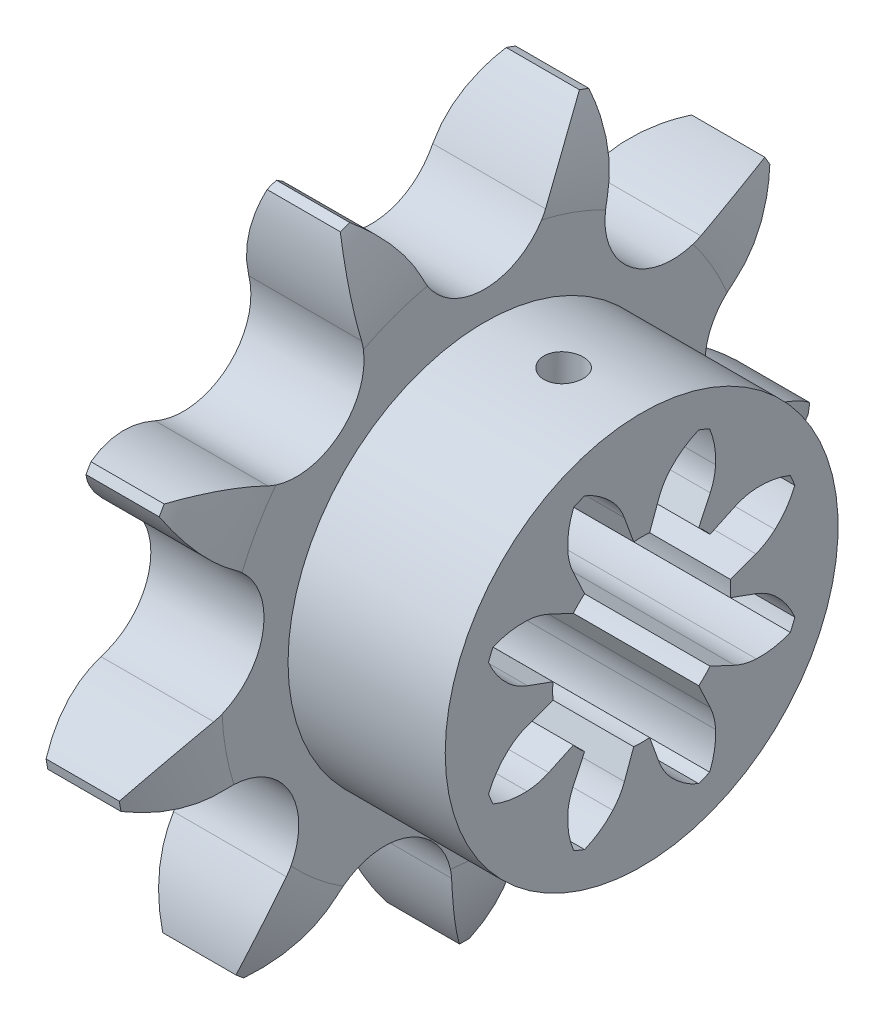
SolidWorks part; units mm, degrees
material "Barra Redonda SAE 1020 - 2\""
ref_plane "Plano frontal" through (0, 0, 0) normal (0, 0, 1) x (1, 0, 0)
ref_plane "Plano superior" through (0, 0, 0) normal (0, 1, 0) x (1, 0, 0)
ref_plane "Plano direito" through (0, 0, 0) normal (1, 0, 0) x (0, 0, -1)
sketch "Esboço1" plane through (0, 0, 0) normal (0, 0, 1) x (1, 0, 0)
  line L0 (-35, 0) -> (0, 0) construction
  line L1 (0, 0) -> (0, 16.7129)
  line L2 (0, 0) -> (17.2, 0)
  line L3 (7.2, 12.5) -> (7.2, 16.7129)
  line L4 (5.93, 22.2487) -> (1.27, 22.2487)
  line L5 (17.2, 0) -> (35, 0) construction
  line L8 (7.2, 12.5) -> (17.2, 12.5)
  line L9 (17.2, 0) -> (17.2, 12.5)
  arc A0 (0, 16.7129) -> (1.27, 22.2487) centre (12.7, 16.7129) cw
  arc A1 (7.2, 16.7129) -> (5.93, 22.2487) centre (-5.5, 16.7129) ccw
  dimension "D4" = 12.7
  dimension "D1" = 1.27
  dimension "D2" = 1.27
  dimension "D3" = 7.2
  dimension "D5" = 44.4973
  dimension "D6" = 10
  dimension "D7" = 25
revolve "Revolução1" add sketch "Esboço1" angle 360 about L0
sketch "Esboço2" plane through (7.2, 0, 0) normal (1, 0, 0) x (0, 0, -1)
  line L0 (0, 18.6087) -> (3.8949, 16.7925) construction
  line L1 (0, 0) -> (0, 63.7114) construction
  line L2 (0, 18.6087) -> (-10, 18.6087) construction
  line L3 (0, 18.6087) -> (-3.8949, 16.7925) construction
  arc A0 (3.8949, 16.7925) -> (7.8075, 21.3669) centre (14.0756, 12.0451) cw
  arc A1 (3.8949, 16.7925) -> (-3.8949, 16.7925) centre (0, 18.6087) cw
  arc A2 (-3.8949, 16.7925) -> (-7.8075, 21.3669) centre (-14.0756, 12.0451) ccw
  arc A3 (7.8075, 21.3669) -> (-7.8075, 21.3669) centre (0, 0) ccw
  dimension "D2" = 4.2976
  dimension "D4" = 11.2332
  dimension "D5" = 22.7487
  dimension "D1" = 18.6087
  dimension "D3" = 130
extrude "Corte-extrusão1" cut sketch "Esboço2" against normal through all
pattern_circular "PadrãoCircular1" count 9 over 360 about axis through (0, 0, 0) along (1, 0, 0) of "Corte-extrusão1"
sketch "Esboço3" plane through (7.2, 0, 0) normal (1, 0, 0) x (0, 0, -1)
  line L0 (0, 0) -> (0, 12.1456) construction
  line L1 (-0.5068, 5.6423) -> (0, 4.25) construction
  line L2 (-0.5068, 5.6423) -> (-1.0979, 7.2665)
  line L3 (0.5068, 5.6423) -> (1.0979, 7.2665)
  line L4 (3.6314, 4.348) -> (4.3619, 5.9145)
  line L5 (4.348, 3.6314) -> (5.9145, 4.3619)
  line L6 (5.6423, 0.5068) -> (7.2665, 1.0979)
  line L7 (5.6423, -0.5068) -> (7.2665, -1.0979)
  line L8 (4.348, -3.6314) -> (5.9145, -4.3619)
  line L9 (3.6314, -4.348) -> (4.3619, -5.9145)
  line L10 (0.5068, -5.6423) -> (1.0979, -7.2665)
  line L11 (-0.5068, -5.6423) -> (-1.0979, -7.2665)
  line L12 (-3.6314, -4.348) -> (-4.3619, -5.9145)
  line L13 (-4.348, -3.6314) -> (-5.9145, -4.3619)
  line L14 (-5.6423, -0.5068) -> (-7.2665, -1.0979)
  line L15 (-5.6423, 0.5068) -> (-7.2665, 1.0979)
  line L16 (-4.348, 3.6314) -> (-5.9145, 4.3619)
  line L17 (-3.6314, 4.348) -> (-4.3619, 5.9145)
  arc A0 (-9.4582, 4.3245) -> (-9.7459, 3.6301) centre (0, 0) ccw construction
  circle A1 centre (0, 0) radius 7.54 construction
  circle A2 centre (0, 0) radius 5.665 construction
  circle A3 centre (0, 0) radius 4.25 construction
  arc A4 (-3.6301, 9.7459) -> (-1.833, 8.4832) centre (-5.5475, 5.1065) cw
  arc A5 (1.833, 8.4832) -> (1.0979, 7.2665) centre (4.556, 6.0079) ccw
  arc A6 (-1.833, 8.4832) -> (-1.0979, 7.2665) centre (-4.556, 6.0079) cw
  arc A7 (3.6301, 9.7459) -> (1.833, 8.4832) centre (5.5475, 5.1065) ccw
  arc A8 (-0.5068, 5.6423) -> (0.5068, 5.6423) centre (0, 0) cw
  arc A9 (4.3245, 9.4582) -> (3.6301, 9.7459) centre (0, 0) ccw construction
  arc A10 (9.7459, 3.6301) -> (9.4582, 4.3245) centre (0, 0) ccw
  arc A11 (4.3245, 9.4582) -> (4.7025, 7.2947) centre (-0.3118, 7.5335) cw
  arc A12 (9.4582, 4.3245) -> (7.2947, 4.7025) centre (7.5335, -0.3118) ccw
  arc A13 (7.2947, 4.7025) -> (5.9145, 4.3619) centre (7.4698, 1.0266) ccw
  arc A14 (4.7025, 7.2947) -> (4.3619, 5.9145) centre (1.0266, 7.4698) cw
  arc A15 (3.6314, 4.348) -> (4.348, 3.6314) centre (0, 0) cw
  arc A16 (9.4582, -4.3245) -> (9.7459, -3.6301) centre (0, 0) ccw
  arc A17 (9.7459, 3.6301) -> (8.4832, 1.833) centre (5.1065, 5.5475) cw
  arc A18 (9.7459, -3.6301) -> (8.4832, -1.833) centre (5.1065, -5.5475) ccw
  arc A19 (8.4832, -1.833) -> (7.2665, -1.0979) centre (6.0079, -4.556) ccw
  arc A20 (8.4832, 1.833) -> (7.2665, 1.0979) centre (6.0079, 4.556) cw
  arc A21 (5.6423, 0.5068) -> (5.6423, -0.5068) centre (0, 0) cw
  arc A22 (3.6301, -9.7459) -> (4.3245, -9.4582) centre (0, 0) ccw
  arc A23 (9.4582, -4.3245) -> (7.2947, -4.7025) centre (7.5335, 0.3118) cw
  arc A24 (4.3245, -9.4582) -> (4.7025, -7.2947) centre (-0.3118, -7.5335) ccw
  arc A25 (4.7025, -7.2947) -> (4.3619, -5.9145) centre (1.0266, -7.4698) ccw
  arc A26 (7.2947, -4.7025) -> (5.9145, -4.3619) centre (7.4698, -1.0266) cw
  arc A27 (4.348, -3.6314) -> (3.6314, -4.348) centre (0, 0) cw
  arc A28 (-4.3245, -9.4582) -> (-3.6301, -9.7459) centre (0, 0) ccw
  arc A29 (3.6301, -9.7459) -> (1.833, -8.4832) centre (5.5475, -5.1065) cw
  arc A30 (-3.6301, -9.7459) -> (-1.833, -8.4832) centre (-5.5475, -5.1065) ccw
  arc A31 (-1.833, -8.4832) -> (-1.0979, -7.2665) centre (-4.556, -6.0079) ccw
  arc A32 (1.833, -8.4832) -> (1.0979, -7.2665) centre (4.556, -6.0079) cw
  arc A33 (0.5068, -5.6423) -> (-0.5068, -5.6423) centre (0, 0) cw
  arc A34 (-9.7459, -3.6301) -> (-9.4582, -4.3245) centre (0, 0) ccw
  arc A35 (-4.3245, -9.4582) -> (-4.7025, -7.2947) centre (0.3118, -7.5335) cw
  arc A36 (-9.4582, -4.3245) -> (-7.2947, -4.7025) centre (-7.5335, 0.3118) ccw
  arc A37 (-7.2947, -4.7025) -> (-5.9145, -4.3619) centre (-7.4698, -1.0266) ccw
  arc A38 (-4.7025, -7.2947) -> (-4.3619, -5.9145) centre (-1.0266, -7.4698) cw
  arc A39 (-3.6314, -4.348) -> (-4.348, -3.6314) centre (0, 0) cw
  arc A41 (-9.7459, -3.6301) -> (-8.4832, -1.833) centre (-5.1065, -5.5475) cw
  arc A42 (-9.7459, 3.6301) -> (-8.4832, 1.833) centre (-5.1065, 5.5475) ccw
  arc A43 (-8.4832, 1.833) -> (-7.2665, 1.0979) centre (-6.0079, 4.556) ccw
  arc A44 (-8.4832, -1.833) -> (-7.2665, -1.0979) centre (-6.0079, -4.556) cw
  arc A45 (-5.6423, -0.5068) -> (-5.6423, 0.5068) centre (0, 0) cw
  arc A46 (-3.6301, 9.7459) -> (-4.3245, 9.4582) centre (0, 0) ccw construction
  arc A47 (-9.4582, 4.3245) -> (-7.2947, 4.7025) centre (-7.5335, -0.3118) cw
  arc A48 (-4.3245, 9.4582) -> (-4.7025, 7.2947) centre (0.3118, 7.5335) ccw
  arc A49 (-4.7025, 7.2947) -> (-4.3619, 5.9145) centre (-1.0266, 7.4698) ccw
  arc A50 (-7.2947, 4.7025) -> (-5.9145, 4.3619) centre (-7.4698, 1.0266) cw
  arc A51 (-4.348, 3.6314) -> (-3.6314, 4.348) centre (0, 0) cw
  arc A52 (-9.4582, 4.3245) -> (-9.7459, 3.6301) centre (0, 0) ccw
  arc A54 (-3.6301, 9.7459) -> (-4.3245, 9.4582) centre (0, 0) ccw
  arc A55 (4.3245, 9.4582) -> (3.6301, 9.7459) centre (0, 0) ccw
  arc A56 (9.7459, 3.6301) -> (9.4582, 4.3245) centre (0, 0) ccw construction
  arc A57 (9.4582, -4.3245) -> (9.7459, -3.6301) centre (0, 0) ccw construction
  arc A58 (3.6301, -9.7459) -> (4.3245, -9.4582) centre (0, 0) ccw construction
  arc A59 (-4.3245, -9.4582) -> (-3.6301, -9.7459) centre (0, 0) ccw construction
  arc A60 (-9.7459, -3.6301) -> (-9.4582, -4.3245) centre (0, 0) ccw construction
  point P110 (0, 0)
  dimension "D1" = 20.8
  dimension "D2" = 15.08
  dimension "D3" = 11.33
  dimension "D4" = 8.5
  dimension "D6" = 5.02
  dimension "D7" = 3.68
  dimension "D5" = 20
  dimension "D8" = 8
extrude "Corte-extrusão2" cut sketch "Esboço3" along normal through all from surface at -7.2 starting at face at (0, 0, 0)
hole_wizard "Furo roscado de M32" positions "3DSketch2" profile "Esboço6" tap size "M3" standard "ISO"
sketch3d "3DSketch2"
  line L0 (5.93, 21.0131, 7.311) -> (1.27, 21.0131, 7.311) construction
  point P0 (12.2, 12.4999, -0.0355)
  dimension "D1" = 5
  dimension "D2" = 11.2448
sketch "Esboço6" plane through (12.2, 12.4999, -0.0355) normal (1, 0, 0) x (0, 0.0028, 1)
  line L0 (0, 0) -> (0, 9.2511)
  line L1 (0, 9.2511) -> (1.25, 8.5)
  line L2 (1.25, 8.5) -> (1.25, 0)
  line L5 (1.25, 0) -> (0, 0)
  line L10 (0, 9.2511) -> (-1.25, 8.5) construction
  line L11 (0, -6.35) -> (0, 107.95) construction
  dimension "Tap Drill Dia." = 2.5
  dimension "Tap Drill Depth" = 8.5
  dimension "Drill Angle" = 118
cosmetic thread "Rosca de furo2" parameters "D1"=6, "D2"=3
